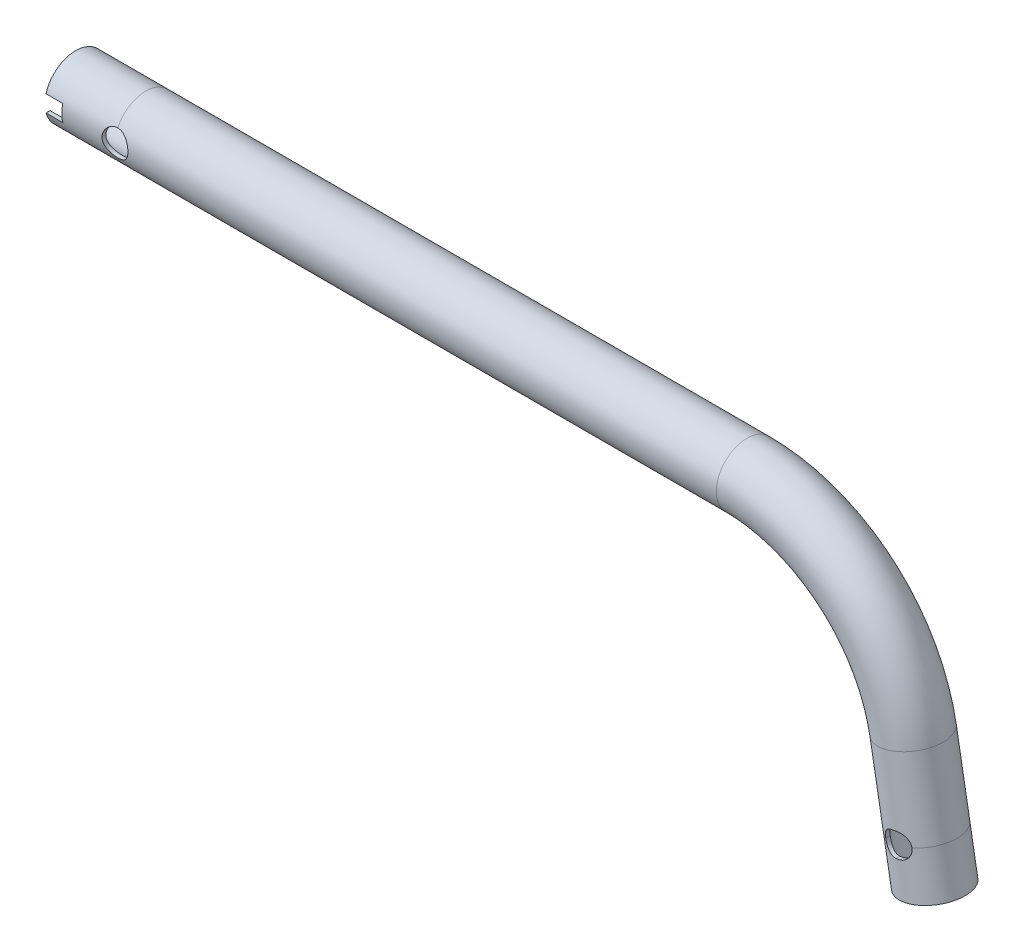
SolidWorks part; units mm, degrees
ref_plane "Front Plane" through (0, 0, 0) normal (0, 0, 1) x (1, 0, 0)
ref_plane "Top Plane" through (0, 0, 0) normal (0, 1, 0) x (1, 0, 0)
ref_plane "Right Plane" through (0, 0, 0) normal (1, 0, 0) x (0, 0, -1)
sketch "Sketch1" plane through (0, 0, 0) normal (0, 0, 1) x (1, 0, 0)
  line L0 (0, 0) -> (185.3734, 0)
  line L1 (236.5834, -42.9703) -> (240.75, -66.6)
  line L2 (0, 0) -> (-21.6, 0)
  line L3 (240.75, -66.6) -> (243.2362, -80.7)
  arc A0 (236.5834, -42.9703) -> (185.3734, 0) centre (185.3734, -52) ccw
  point P10 (240.75, -66.6)
  dimension "D2" = 52
  dimension "D1" = 80
  dimension "D3" = 240.75
  dimension "D4" = 66.6
  dimension "D5" = 21.6
  dimension "D6" = 80.7
ref_plane "Plane1" through (-21.6, 0, 0) normal (-1, 0, 0) x (0, 0, 1)
sketch "Sketch2" plane through (-21.6, 0, 0) normal (-1, 0, 0) x (0, 0, 1)
  circle A0 centre (0, 0) radius 9.5
  circle A1 centre (0, 0) radius 8.3
  dimension "D1" = 1.2
sweep "Sweep1" add profiles "Sketch2" path "Sketch1"
sketch "Sketch3" plane through (0, 0, 0) normal (0, 0, 1) x (1, 0, 0)
  line L0 (240.75, -66.6) -> (244.7877, -65.888) construction
  line L1 (231.3943, -68.2497) -> (250.1057, -64.9503) construction
  line L2 (240.75, -66.6) -> (240.1335, -63.1039) construction
  line L3 (244.8022, -65.9703) -> (244.7732, -65.8058)
  line L4 (240.7186, -62.9667) -> (239.5368, -63.1751)
  line L5 (236.6978, -67.2297) -> (236.7268, -67.3942)
  line L6 (240.7814, -70.2333) -> (241.9632, -70.0249)
  arc A0 (240.7814, -70.2333) -> (236.7268, -67.3942) centre (240.1736, -66.7865) cw
  arc A1 (241.9632, -70.0249) -> (244.8022, -65.9703) centre (241.3554, -66.5781) ccw
  arc A2 (244.7732, -65.8058) -> (240.7186, -62.9667) centre (241.3264, -66.4135) ccw
  arc A3 (239.5368, -63.1751) -> (236.6978, -67.2297) centre (240.1446, -66.6219) ccw
  point P8 (244.7877, -65.888)
  point P14 (245.41, -69.4172)
  point P17 (244.1654, -62.3589)
  point P20 (236.09, -63.7828)
  dimension "D6" = 3.5
  dimension "D1" = 4.1
  dimension "D2" = 3.55
  dimension "D3" = 90
  dimension "D4" = 7.1671
  dimension "D5" = 8.2
extrude "Cut-Extrude1" cut sketch "Sketch3" against normal up to next and the other way up to next
sketch "Sketch4" plane through (0, 0, 0) normal (0, 0, 1) x (1, 0, 0)
  line L0 (0, -9.5) -> (0, 9.5) construction
  circle A0 centre (0, 0) radius 4
extrude "Cut-Extrude2" cut sketch "Sketch4" along normal up to next
sketch "Sketch5" plane through (0, 0, 0) normal (0, 0, 1) x (1, 0, 0)
  line L0 (-21.6, 0) -> (-21.6, 2.555)
  line L1 (-21.6, 9.5) -> (-21.6, -9.5) construction
  line L2 (-21.6, 2.555) -> (-16.4, 2.555)
  line L3 (-16.4, 2.555) -> (-16.4, -2.555)
  line L4 (-16.4, -2.555) -> (-21.6, -2.555)
  line L5 (-21.6, -2.555) -> (-21.6, 0)
  dimension "D1" = 5.2
  dimension "D2" = 5.11
extrude "Cut-Extrude3" cut sketch "Sketch5" against normal through all and the other way through all
